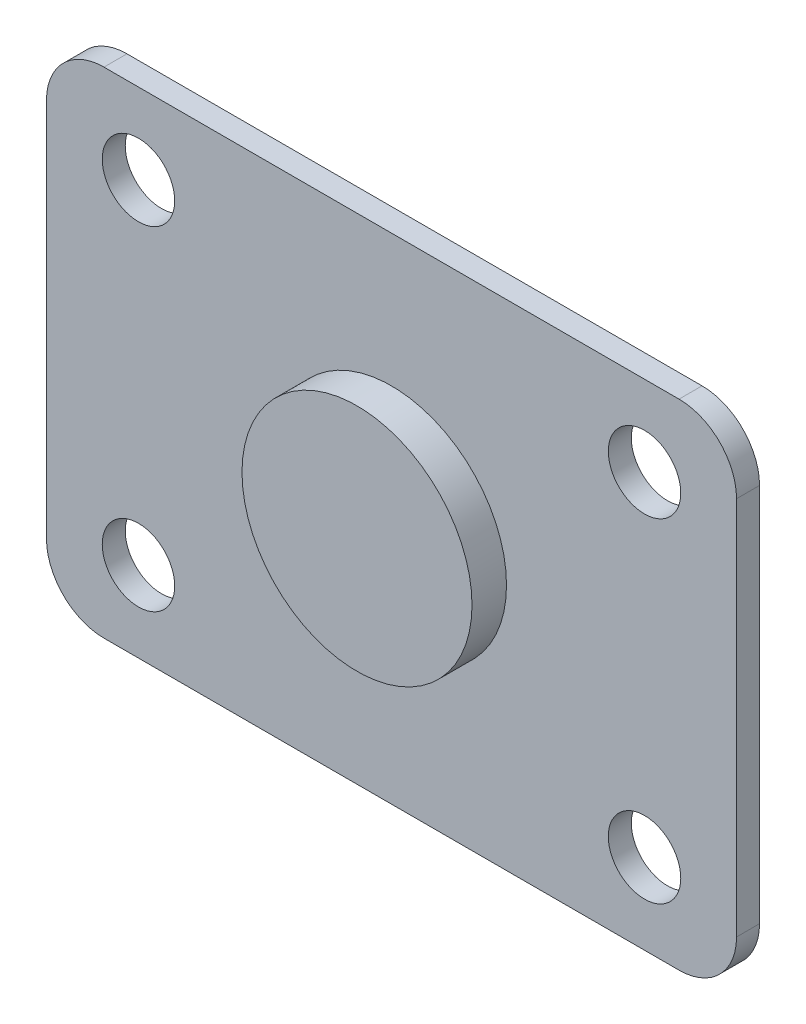
SolidWorks part; units mm, degrees
ref_plane "前视基准面" through (0, 0, 0) normal (0, 0, 1) x (1, 0, 0)
ref_plane "上视基准面" through (0, 0, 0) normal (0, 1, 0) x (1, 0, 0)
ref_plane "右视基准面" through (0, 0, 0) normal (1, 0, 0) x (0, 0, -1)
sketch "草图1" plane through (0, 0, 0) normal (0, 0, 1) x (1, 0, 0)
  line L1 (-30, 21.5) -> (30, 21.5)
  line L2 (-30, 21.5) -> (-30, -21.5)
  line L3 (-30, -21.5) -> (30, -21.5)
  line L4 (30, 21.5) -> (30, -21.5)
  dimension "D1" = 60
  dimension "D2" = 43
  dimension "D3" = 21.5
  dimension "D4" = 30
extrude "凸台-拉伸1" add sketch "草图1" along normal blind 2
sketch "草图2" plane through (0, 0, 2) normal (0, 0, 1) x (1, 0, 0)
  circle A0 centre (0, 0) radius 10
  dimension "D1" = 20
extrude "凸台-拉伸2" add sketch "草图2" along normal blind 3
fillet "圆角1" radius 5 4 edges at (-30, -21.5, 1) (-30, 21.5, 1) (30, -21.5, 1) (30, 21.5, 1)
sketch "草图3" plane through (0, 0, 0) normal (0, 0, -1) x (-1, 0, 0)
  line L1 (-22, 14.5) -> (22, 14.5) construction
  line L2 (-22, 14.5) -> (-22, -14.5) construction
  line L3 (-22, -14.5) -> (22, -14.5) construction
  line L4 (22, 14.5) -> (22, -14.5) construction
  circle A0 centre (22, 14.5) radius 3.15
  circle A1 centre (22, -14.5) radius 3.15
  circle A2 centre (-22, 14.5) radius 3.15
  circle A3 centre (-22, -14.5) radius 3.15
  dimension "D5" = 6.3
  dimension "D1" = 29
  dimension "D2" = 44
  dimension "D3" = 14.5
  dimension "D4" = 22
extrude "切除-拉伸1" cut sketch "草图3" against normal blind 3
